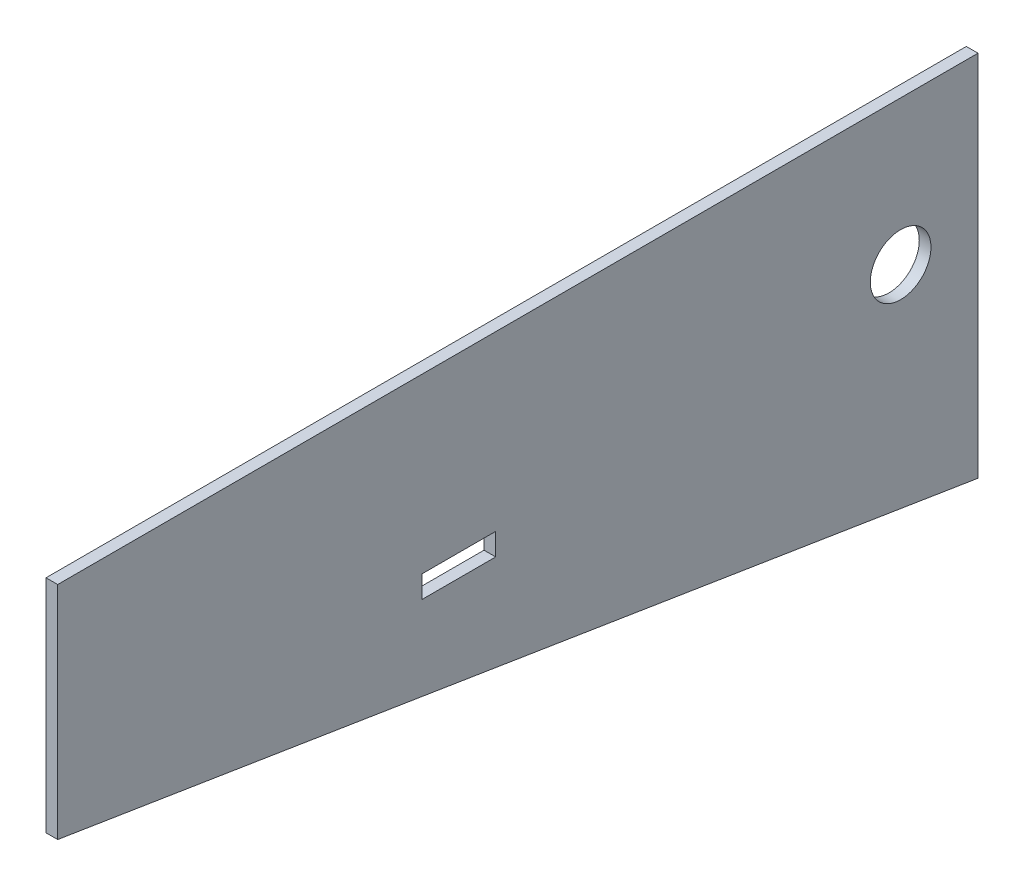
SolidWorks part; units mm, degrees
ref_plane "Front Plane" through (0, 0, 0) normal (0, 0, 1) x (1, 0, 0)
ref_plane "Top Plane" through (0, 0, 0) normal (0, 1, 0) x (1, 0, 0)
ref_plane "Right Plane" through (0, 0, 0) normal (1, 0, 0) x (0, 0, -1)
sketch "Sketch1" plane through (0, 0, 0) normal (1, 0, 0) x (0, 0, -1)
  line L0 (0, 17.8493) -> (0, 30)
  line L1 (0, 0) -> (0, 4.4613)
  line L2 (0, 4.4613) -> (0, 9.4613)
  line L3 (0, 9.4613) -> (0, 17.8493)
  line L4 (0, 30) -> (125, 30)
  line L5 (125, 30) -> (125, -20)
  line L6 (125, -20) -> (0, 0)
  dimension "D1" = 30
  dimension "D2" = 125
  dimension "D3" = 125
  dimension "D4" = 50
extrude "Boss-Extrude1" add sketch "Sketch1" along normal blind 1.5875 contours L4 L5 L6 L1 L2 L3 L0
sketch "Sketch2" plane through (1.5875, 0, 0) normal (1, 0, 0) x (0, 0, -1)
  line L0 (0, 30) -> (125, 30) construction
  line L1 (125, 30) -> (125, -20) construction
  line L3 (49.49, 6.51) -> (59.49, 6.51)
  line L4 (49.49, 6.51) -> (49.49, 3.5)
  line L5 (49.49, 3.5) -> (59.49, 3.5)
  line L6 (59.49, 6.51) -> (59.49, 3.5)
  line L7 (49.49, 6.51) -> (59.49, 3.5) construction
  line L8 (49.49, 3.5) -> (59.49, 6.51) construction
  circle A0 centre (114.49, 10.38) radius 4.12
  point P7 (54.49, 5.005)
  point P12 (59.49, 5.005)
  dimension "D3" = 8.24
  dimension "D1" = 19.62
  dimension "D2" = 10.51
  dimension "D4" = 55
  dimension "D5" = 10
  dimension "D6" = 3.01
  dimension "D7" = 23.49
extrude "Cut-Extrude1" cut sketch "Sketch2" against normal blind 1.5875
